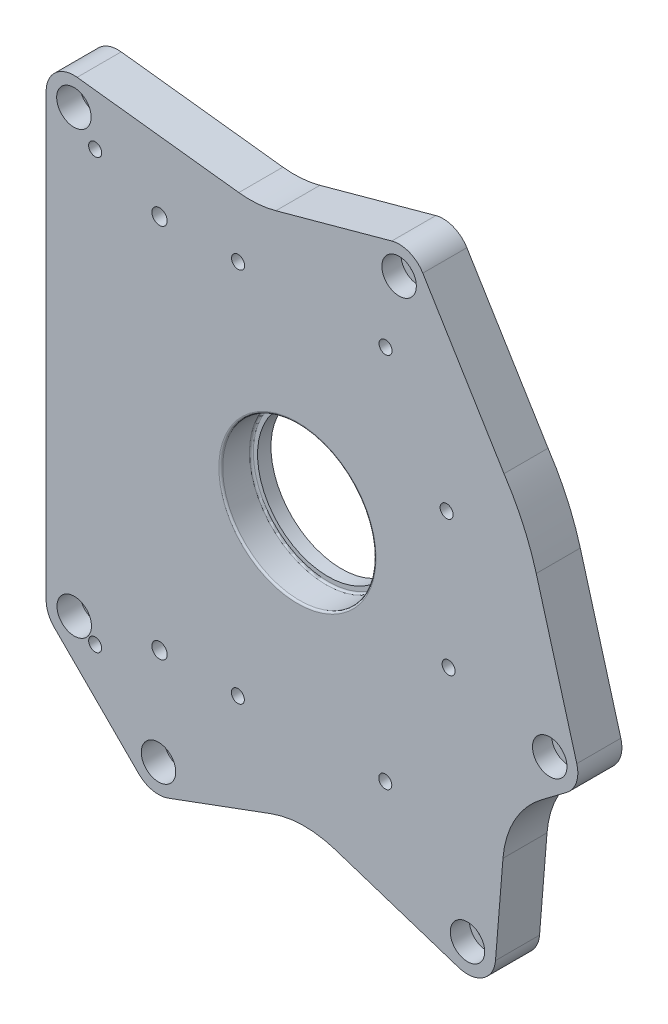
SolidWorks part; units mm, degrees
material "6061-T6 (SS)"
ref_plane "Front Plane" through (0, 0, 0) normal (0, 0, 1) x (1, 0, 0)
ref_plane "Top Plane" through (0, 0, 0) normal (0, 1, 0) x (1, 0, 0)
ref_plane "Right Plane" through (0, 0, 0) normal (1, 0, 0) x (0, 0, -1)
sketch "Sketch1" plane through (0, 0, 0) normal (0, 0, 1) x (1, 0, 0)
  line L0 (84.2211, -163.4901) -> (2.6993, -136.8316)
  line L1 (-67.4584, -162.7302) -> (2.6993, -136.8316)
  line L2 (-82.9108, -159.3414) -> (-126.9141, -115.3364)
  line L3 (140.5448, -56.1387) -> (109.1493, -79.774)
  line L4 (103.4012, -150.7323) -> (109.1493, -79.774)
  line L5 (145.8454, -40.4558) -> (124.6838, 34.9416)
  line L6 (65.4504, 141.1198) -> (107.841, 71.6428)
  line L9 (49.2431, 147.5528) -> (-20.7968, 128.3749)
  line L13 (-115.0226, 139.4368) -> (-20.7968, 128.3749)
  line L14 (-131.2133, 125.0355) -> (-131.2102, -104.9645)
  arc A2 (-115.0226, 139.4368) -> (-131.2133, 125.0355) centre (-116.7133, 125.0357) ccw
  circle A3 centre (-116.7133, 125.0357) radius 3.5 construction
  arc A6 (65.4504, 141.1198) -> (49.2431, 147.5528) centre (53.0725, 133.5676) ccw
  circle A7 centre (-76.5534, 103.7539) radius 2.5 construction
  arc A9 (-131.2102, -104.9645) -> (-126.9141, -115.3364) centre (-116.5415, -104.9643) ccw
  circle A10 centre (-116.5415, -104.9643) radius 3.5 construction
  arc A12 (-82.9108, -159.3414) -> (-67.4584, -162.7302) centre (-72.5383, -148.9692) ccw
  circle A13 centre (-72.5383, -148.9692) radius 3.5 construction
  arc A15 (84.2211, -163.4901) -> (103.4012, -150.7323) centre (88.7803, -149.548) ccw
  arc A17 (140.5448, -56.1387) -> (145.8454, -40.4558) centre (131.7224, -44.4197) ccw
  circle A18 centre (59.1026, -114.9804) radius 2.5 construction
  circle A23 centre (88.7803, -149.548) radius 3.5 construction
  circle A27 centre (131.7224, -44.4197) radius 3.5 construction
  arc A30 (124.6838, 34.9416) -> (107.841, 71.6428) centre (-0.017, -0.0702) ccw
  circle A31 centre (53.0725, 133.5676) radius 3.5 construction
  dimension "D1" = 14.5
  dimension "D2" = 7
  dimension "D3" = 5
extrude "Boss-Extrude1" add sketch "Sketch1" along normal blind 23 contours L5 A30 L6 A6 L9 L13 A2 L14 A9 L2 A12 L1 L0 A15 L4 L3 A17 A31 A3 A7 A10 A13 A18 A23 A27
fillet "Fillet2" radius 50.8 3 edges at (-20.7968, 128.3749, 11.5) (109.1493, -79.774, 11.5) (2.6993, -136.8316, 11.5)
sketch "Sketch2" plane through (0, 0, 23) normal (0, 0, -1) x (-1, 0, 0)
  circle A0 centre (0, 0) radius 40.05
  dimension "D1" = 80.1
extrude "Cut-Extrude1" cut sketch "Sketch2" along normal blind 16
sketch "Sketch5" plane through (0, 0, 23) normal (0, 0, -1) x (-1, 0, 0)
  circle A0 centre (0, 0) radius 36.83
  dimension "D1" = 73.66
extrude "Cut-Extrude2" cut sketch "Sketch5" along normal blind 25.4
sketch "Sketch6" plane through (0, 0, 0) normal (0, 0, 1) x (1, 0, 0)
  circle A0 centre (0, 0) radius 50.8 construction
  point P14 (0, 0)
  dimension "D2" = 101.6
fillet "Fillet5" radius 1 1 edges at (-40.05, 0, 23)
fillet "Fillet6" radius 1 1 edges at (-40.05, 0, 7)
sketch "Sketch43" plane through (0, 0, 23) normal (0, 0, 1) x (1, 0, 0)
  line L13 (0, 0) -> (150.4649, 0) construction
  line L14 (-31.12, -98.35) -> (-105.6166, -112.2929) construction
  line L15 (-31, 98) -> (-105.6166, 111.6261) construction
  line L16 (-105.6166, -112.2929) -> (-105.6166, 111.6261) construction
  line L17 (0, 0) -> (-105.6166, 111.6261) construction
  line L18 (-31, 98) -> (0, 0) construction
  line L19 (0, 0) -> (46, 97.92) construction
  line L20 (77.9, 39.75) -> (0, 0) construction
  line L21 (0, 0) -> (-72, -98.1221) construction
  line L22 (0, 0) -> (78.925, -30.46) construction
  line L23 (45.85, -98.52) -> (0, 0) construction
  line L24 (0, 0) -> (-72, 97.9779) construction
  line L25 (0, 0) -> (-31.12, -98.35) construction
  line L26 (-105.6166, -112.2929) -> (0, 0) construction
  circle A8 centre (0, 0) radius 46.4211 construction
  circle A12 centre (-46.643, -71.23) radius 11.3319 construction
  circle A13 centre (-72, 97.9779) radius 3.9701
  circle A14 centre (-72, -98.1221) radius 3.9701
  circle A15 centre (-105.6166, 111.6261) radius 3
  circle A16 centre (-31, 98) radius 3
  circle A17 centre (46, 97.92) radius 3
  circle A18 centre (77.9, 39.75) radius 3
  circle A19 centre (78.925, -30.46) radius 3
  circle A20 centre (45.85, -98.52) radius 3
  circle A21 centre (-31.12, -98.35) radius 3
  circle A22 centre (-105.6166, -112.2929) radius 3
  circle A23 centre (0, 0) radius 36.83 construction
  dimension "D2" = 45.85
  dimension "D3" = 31.12
  dimension "D1" = 98.52
  dimension "D4" = 98.35
  dimension "D5" = 98.1221
  dimension "D6" = 72
  dimension "D7" = 105.6166
  dimension "D8" = 105.6166
  dimension "D9" = 72
  dimension "D10" = 31
  dimension "D11" = 46
  dimension "D12" = 77.9
  dimension "D13" = 78.925
  dimension "D14" = 39.75
  dimension "D15" = 30.46
  dimension "D16" = 97.92
  dimension "D17" = 98
  dimension "D18" = 97.9779
  dimension "D19" = 111.6261
  dimension "D20" = 112.2929
  dimension "D21" = 196.1
  dimension "D22" = 7.9403
  dimension "D23" = 6
sketch "Sketch59" plane through (0, 0, 23) normal (0, 0, 1) x (1, 0, 0)
  line L0 (145.8454, -40.4558) -> (124.6838, 34.9416) construction
  line L1 (140.5448, -56.1387) -> (127.387, -66.0442) construction
  line L2 (103.4012, -150.7323) -> (107.3061, -102.5275) construction
  line L3 (84.2211, -163.4901) -> (19.4993, -142.3254) construction
  line L4 (-67.4584, -162.7302) -> (-13.8824, -142.9527) construction
  line L5 (-82.9108, -159.3414) -> (-126.9141, -115.3364) construction
  line L6 (65.4504, 141.1198) -> (107.841, 71.6428) construction
  line L7 (49.2431, 147.5528) -> (-11.269, 130.9837) construction
  line L8 (-115.0226, 139.4368) -> (-30.608, 129.5267) construction
  line L9 (-131.2133, 125.0355) -> (-131.2102, -104.9645) construction
  line L10 (145.8454, -40.4558) -> (124.6838, 34.9416)
  line L11 (140.5448, -56.1387) -> (127.387, -66.0442)
  line L12 (103.4012, -150.7323) -> (107.3061, -102.5275)
  line L13 (84.2211, -163.4901) -> (19.4993, -142.3254)
  line L14 (-67.4584, -162.7302) -> (-13.8824, -142.9527)
  line L15 (-82.9108, -159.3414) -> (-126.9141, -115.3364)
  line L16 (65.4504, 141.1198) -> (107.841, 71.6428)
  line L17 (49.2431, 147.5528) -> (-11.269, 130.9837)
  line L18 (-115.0226, 139.4368) -> (-30.608, 129.5267)
  line L19 (-131.2133, 125.0355) -> (-131.2102, -104.9645)
  line L30 (49.2431, 147.5528) -> (-20.7968, 128.3749)
  line L31 (107.841, 71.6428) -> (65.4504, 141.1198)
  line L32 (145.8454, -40.4558) -> (124.6838, 34.9416)
  line L33 (109.1493, -79.774) -> (140.5448, -56.1387)
  line L34 (103.4012, -150.7323) -> (109.1493, -79.774)
  line L35 (2.6993, -136.8316) -> (84.2211, -163.4901)
  line L36 (-67.4584, -162.7302) -> (2.6993, -136.8316)
  line L37 (-126.9141, -115.3364) -> (-82.9108, -159.3414)
  line L38 (-131.2133, 125.0355) -> (-131.2102, -104.9645)
  line L39 (-20.7968, 128.3749) -> (-115.0226, 139.4368)
  line L40 (49.2431, 147.5528) -> (-20.7968, 128.3749)
  line L41 (107.841, 71.6428) -> (65.4504, 141.1198)
  line L42 (145.8454, -40.4558) -> (124.6838, 34.9416)
  line L43 (109.1493, -79.774) -> (140.5448, -56.1387)
  line L44 (103.4012, -150.7323) -> (109.1493, -79.774)
  line L45 (2.6993, -136.8316) -> (84.2211, -163.4901)
  line L46 (-67.4584, -162.7302) -> (2.6993, -136.8316)
  line L47 (-126.9141, -115.3364) -> (-82.9108, -159.3414)
  line L48 (-131.2133, 125.0355) -> (-131.2102, -104.9645)
  line L49 (-20.7968, 128.3749) -> (-115.0226, 139.4368)
  arc A0 (124.6838, 34.9416) -> (107.841, 71.6428) centre (-0.017, -0.0702) ccw construction
  arc A1 (140.5448, -56.1387) -> (145.8454, -40.4558) centre (131.7224, -44.4197) ccw construction
  arc A2 (127.387, -66.0442) -> (107.3061, -102.5275) centre (157.9402, -106.6292) ccw construction
  arc A3 (84.2211, -163.4901) -> (103.4012, -150.7323) centre (88.7803, -149.548) ccw construction
  arc A4 (19.4993, -142.3254) -> (-13.8824, -142.9527) centre (3.7099, -190.6093) ccw construction
  arc A5 (-82.9108, -159.3414) -> (-67.4584, -162.7302) centre (-72.5383, -148.9692) ccw construction
  arc A6 (-131.2102, -104.9645) -> (-126.9141, -115.3364) centre (-116.5415, -104.9643) ccw construction
  arc A7 (65.4504, 141.1198) -> (49.2431, 147.5528) centre (53.0725, 133.5676) ccw construction
  arc A8 (-30.608, 129.5267) -> (-11.269, 130.9837) centre (-24.6849, 179.9802) ccw construction
  arc A9 (-115.0226, 139.4368) -> (-131.2133, 125.0355) centre (-116.7133, 125.0357) ccw construction
  arc A10 (124.6838, 34.9416) -> (107.841, 71.6428) centre (-0.017, -0.0702) ccw
  arc A11 (140.5448, -56.1387) -> (145.8454, -40.4558) centre (131.7224, -44.4197) ccw
  arc A12 (127.387, -66.0442) -> (107.3061, -102.5275) centre (157.9402, -106.6292) ccw
  arc A13 (84.2211, -163.4901) -> (103.4012, -150.7323) centre (88.7803, -149.548) ccw
  arc A14 (19.4993, -142.3254) -> (-13.8824, -142.9527) centre (3.7099, -190.6093) ccw
  arc A15 (-82.9108, -159.3414) -> (-67.4584, -162.7302) centre (-72.5383, -148.9692) ccw
  arc A16 (-131.2102, -104.9645) -> (-126.9141, -115.3364) centre (-116.5415, -104.9643) ccw
  arc A17 (65.4504, 141.1198) -> (49.2431, 147.5528) centre (53.0725, 133.5676) ccw
  arc A18 (-30.608, 129.5267) -> (-11.269, 130.9837) centre (-24.6849, 179.9802) ccw
  arc A19 (-115.0226, 139.4368) -> (-131.2133, 125.0355) centre (-116.7133, 125.0357) ccw
  circle A20 centre (-116.7133, 125.0357) radius 3.5 construction
  circle A21 centre (-76.5534, 103.7539) radius 2.5 construction
  circle A22 centre (-116.5415, -104.9643) radius 3.5 construction
  circle A23 centre (-72.5383, -148.9692) radius 3.5 construction
  circle A24 centre (59.1026, -114.9804) radius 2.5 construction
  circle A25 centre (88.7803, -149.548) radius 3.5 construction
  circle A26 centre (131.7224, -44.4197) radius 3.5 construction
  arc A27 (65.4504, 141.1198) -> (49.2431, 147.5528) centre (53.0725, 133.5676) ccw
  arc A28 (124.6838, 34.9416) -> (107.841, 71.6428) centre (-0.017, -0.0702) ccw
  arc A29 (140.5448, -56.1387) -> (145.8454, -40.4558) centre (131.7224, -44.4197) ccw
  arc A30 (84.2211, -163.4901) -> (103.4012, -150.7323) centre (88.7803, -149.548) ccw
  arc A31 (-82.9108, -159.3414) -> (-67.4584, -162.7302) centre (-72.5383, -148.9692) ccw
  arc A32 (-131.2102, -104.9645) -> (-126.9141, -115.3364) centre (-116.5415, -104.9643) ccw
  arc A33 (-115.0226, 139.4368) -> (-131.2133, 125.0355) centre (-116.7133, 125.0357) ccw
  arc A34 (65.4504, 141.1198) -> (49.2431, 147.5528) centre (53.0725, 133.5676) ccw
  arc A35 (124.6838, 34.9416) -> (107.841, 71.6428) centre (-0.017, -0.0702) ccw
  arc A36 (140.5448, -56.1387) -> (145.8454, -40.4558) centre (131.7224, -44.4197) ccw
  arc A37 (84.2211, -163.4901) -> (103.4012, -150.7323) centre (88.7803, -149.548) ccw
  arc A38 (-82.9108, -159.3414) -> (-67.4584, -162.7302) centre (-72.5383, -148.9692) ccw
  arc A39 (-131.2102, -104.9645) -> (-126.9141, -115.3364) centre (-116.5415, -104.9643) ccw
  arc A40 (-115.0226, 139.4368) -> (-131.2133, 125.0355) centre (-116.7133, 125.0357) ccw
  circle A41 centre (53.0725, 133.5676) radius 3.5 construction
  dimension "D1" = 0
hole_wizard "CBORE for M10 SHCS7" positions "Sketch62" profile "Sketch63" counterbore size "M10" standard "ANSI Metric" end condition through all
sketch "Sketch62" plane through (0, 0, 23) normal (0, 0, 1) x (1, 0, 0)
  point P0 (-116.7133, 125.0357)
  point P3 (-116.5415, -104.9643)
  point P7 (-72.5383, -148.9692)
sketch "Sketch63" plane through (-116.7133, 125.0357, 23) normal (1, 0, 0) x (0, -1, 0)
  line L0 (0, 0) -> (0, 23)
  line L1 (0, 23) -> (5.25, 23)
  line L3 (5.25, 23) -> (5.25, 12)
  line L4 (5.25, 12) -> (9, 12)
  line L5 (9, 12) -> (9, 0)
  line L7 (9, 0) -> (0, 0)
  line L11 (0, -6.35) -> (0, 107.95) construction
  dimension "Thru Hole Dia." = 10.5
  dimension "Thru Hole Depth" = 23
  dimension "C'Bore Dia." = 18
  dimension "C'Bore Depth" = 12
hole_wizard "Tap Drill for M8x1.25 Tap2" positions "Sketch66" profile "Sketch67" hole size "M8x1.25" standard "ANSI Metric" end condition through all
sketch "Sketch66" plane through (0, 0, 23) normal (0, 0, 1) x (1, 0, 0)
  point P0 (46, 97.92)
  point P3 (-31, 98)
  point P6 (-105.6166, 111.6261)
  point P9 (-105.6166, -112.2929)
  point P12 (-31.12, -98.35)
  point P15 (45.85, -98.52)
  point P18 (78.925, -30.46)
  point P21 (77.9, 39.75)
sketch "Sketch67" plane through (46, 97.92, 23) normal (1, 0, 0) x (0, -1, 0)
  line L0 (0, 0) -> (0, 23)
  line L1 (0, 23) -> (3.4, 23)
  line L2 (3.4, 23) -> (3.4, 0)
  line L5 (3.4, 0) -> (0, 0)
  line L11 (0, -6.35) -> (0, 107.95) construction
  dimension "Thru Hole Dia." = 6.8
  dimension "Thru Hole Depth" = 23
hole_wizard "Ø8.0mm Dowel Hole1" positions "Sketch70" profile "Sketch71" hole size "Ø8.0" standard "ANSI Metric"
sketch "Sketch70" plane through (0, 0, 23) normal (0, 0, 1) x (1, 0, 0)
  point P0 (-72, 97.9779)
  point P3 (-72, -98.1221)
sketch "Sketch71" plane through (-72, 97.9779, 23) normal (1, 0, 0) x (0, -1, 0)
  line L0 (0, 0) -> (0, 11.4034)
  line L1 (0, 11.4034) -> (4, 9)
  line L2 (4, 9) -> (4, 0)
  line L5 (4, 0) -> (0, 0)
  line L10 (0, 11.4034) -> (-4, 9) construction
  line L11 (0, -6.35) -> (0, 107.95) construction
  dimension "Hole Dia." = 8
  dimension "Hole Depth" = 9
  dimension "Drill Angle" = 118
hole_wizard "Ø10.0mm Dowel Hole3" positions "Sketch72" profile "Sketch73" hole size "Ø10.0" standard "ANSI Metric"
sketch "Sketch72" plane through (0, 0, 0) normal (0, 0, -1) x (-1, 0, 0)
  point P0 (76.5534, 103.7539)
  point P3 (-59.1026, -114.9804)
sketch "Sketch73" plane through (-76.5534, 103.7539, 0) normal (1, 0, 0) x (0, 1, 0)
  line L0 (0, 0) -> (0, 13.0043)
  line L1 (0, 13.0043) -> (5, 10)
  line L2 (5, 10) -> (5, 0)
  line L5 (5, 0) -> (0, 0)
  line L10 (0, 13.0043) -> (-5, 10) construction
  line L11 (0, -6.35) -> (0, 107.95) construction
  dimension "Hole Dia." = 10
  dimension "Hole Depth" = 10
  dimension "Drill Angle" = 118
hole_wizard "CBORE for M10 SHCS9" positions "Sketch74" profile "Sketch75" counterbore size "M10" standard "ANSI Metric" end condition through all
sketch "Sketch74" plane through (0, 0, 23) normal (0, 0, 1) x (1, 0, 0)
  point P0 (53.0725, 133.5676)
  point P3 (131.7224, -44.4197)
  point P6 (88.7803, -149.548)
sketch "Sketch75" plane through (53.0725, 133.5676, 23) normal (1, 0, 0) x (0, -1, 0)
  line L0 (0, 0) -> (0, 23)
  line L1 (0, 23) -> (5.25, 23)
  line L3 (5.25, 23) -> (5.25, 10)
  line L4 (5.25, 10) -> (9, 10)
  line L5 (9, 10) -> (9, 0)
  line L7 (9, 0) -> (0, 0)
  line L11 (0, -6.35) -> (0, 107.95) construction
  dimension "Thru Hole Dia." = 10.5
  dimension "Thru Hole Depth" = 23
  dimension "C'Bore Dia." = 18
  dimension "C'Bore Depth" = 10
